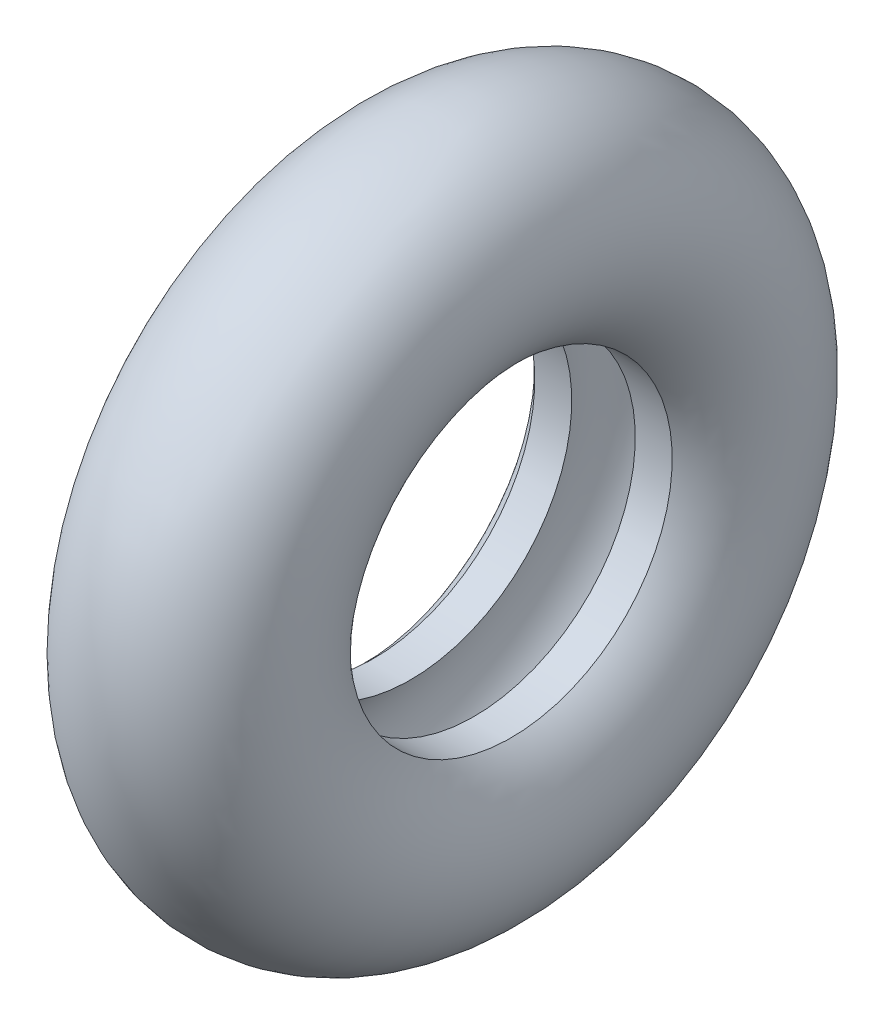
SolidWorks part; units mm, degrees
material "BUTYL"
ref_plane "Plan de face" through (0, 0, 0) normal (0, 0, 1) x (1, 0, 0)
ref_plane "Plan de dessus" through (0, 0, 0) normal (0, 1, 0) x (1, 0, 0)
ref_plane "Plan de droite" through (0, 0, 0) normal (1, 0, 0) x (0, 0, -1)
sketch "Esquisse1" plane through (0, 0, 0) normal (0, 0, 1) x (1, 0, 0)
  line L0 (-106.6081, 0) -> (126.1459, 0) construction
  line L1 (0, 110.4307) -> (0, -134.2158) construction
  line L2 (120.5589, 184.995) -> (-140.6473, 184.995) construction
  line L3 (-36.2137, 85) -> (-16.7432, 85)
  line L4 (16.7432, 85) -> (36.2137, 85)
  arc A0 (36.2137, 85) -> (-36.2137, 85) centre (0, 128.44) ccw
  arc A1 (-16.7432, 85) -> (16.7432, 85) centre (0, 128.44) cw
  dimension "D1" = 113.11
  dimension "D5" = 10
  dimension "D2" = 128.44
  dimension "D3" = 184.995
  dimension "D4" = 85
revolve "Révolution1" add sketch "Esquisse1" angle 360 about L0
